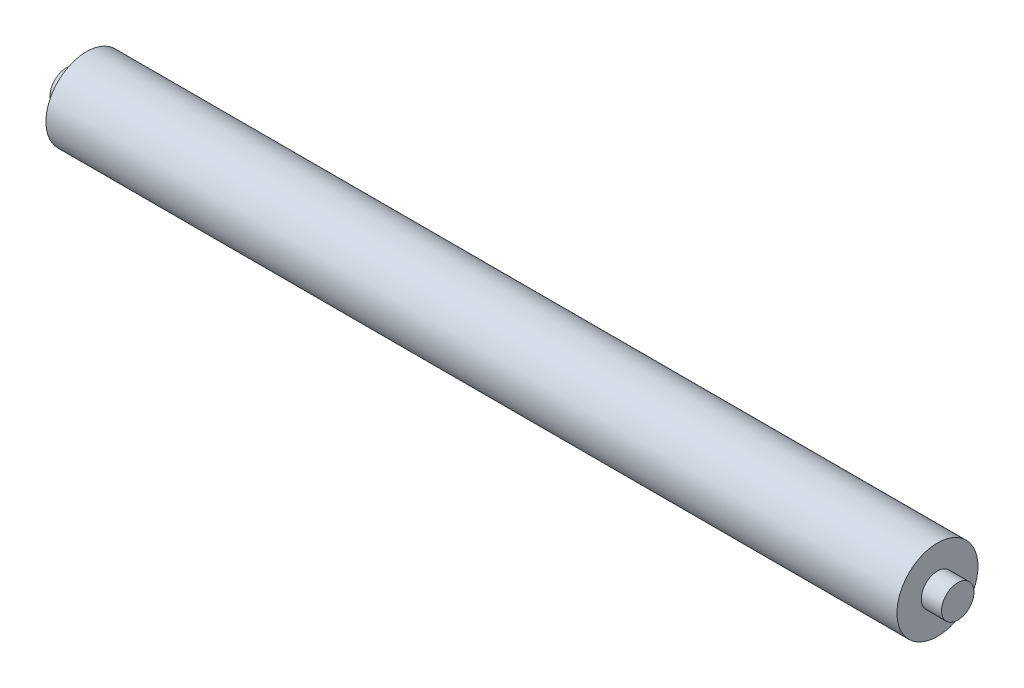
SolidWorks part; units mm, degrees
material "Bronce comercial, UNS C22000 (90-10 bronce)"
ref_plane "Alzado" through (0, 0, 0) normal (0, 0, 1) x (1, 0, 0)
ref_plane "Planta" through (0, 0, 0) normal (0, 1, 0) x (1, 0, 0)
ref_plane "Vista lateral" through (0, 0, 0) normal (1, 0, 0) x (0, 0, -1)
sketch "Croquis1" plane through (0, 0, 0) normal (1, 0, 0) x (0, 0, -1)
  circle A0 centre (0, 0) radius 5
  dimension "D1" = 10
extrude "Saliente-Extruir1" add sketch "Croquis1" along normal mid plane 105
sketch "Croquis2" plane through (0, 0, 0) normal (1, 0, 0) x (0, 0, -1)
  circle A0 centre (0, 0) radius 2
  dimension "D1" = 4
extrude "Saliente-Extruir2" add sketch "Croquis2" along normal mid plane 110
